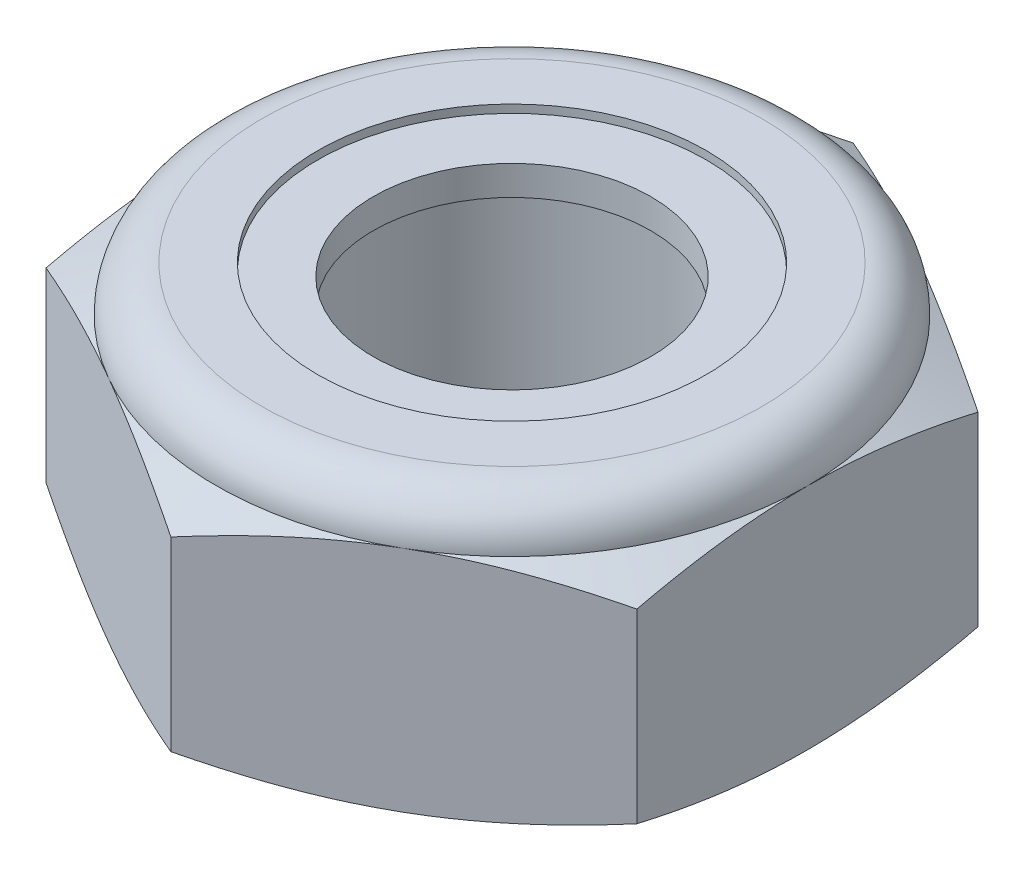
SolidWorks part; units mm, degrees
material "Plain Carbon Steel"
ref_plane "Front" through (0, 0, 0) normal (0, 0, 1) x (1, 0, 0)
ref_plane "Top" through (0, 0, 0) normal (0, 1, 0) x (1, 0, 0)
ref_plane "Right" through (0, 0, 0) normal (1, 0, 0) x (0, 0, -1)
sketch "Sketch1" plane through (0, 0, 0) normal (0, 1, 0) x (1, 0, 0)
  line L1 (0, 6.4158) -> (-5.5563, 3.2079)
  line L2 (-5.5563, 3.2079) -> (-5.5563, -3.2079)
  line L3 (-5.5563, -3.2079) -> (0, -6.4158)
  line L4 (0, -6.4158) -> (5.5562, -3.2079)
  line L5 (5.5562, -3.2079) -> (5.5562, 3.2079)
  line L6 (5.5562, 3.2079) -> (0, 6.4158)
  circle A0 centre (0, 0) radius 5.5563 construction
  dimension "Hex Flats" = 11.1125
extrude "Extrude1" add sketch "Sketch1" along normal blind 5.1594
sketch "Sketch2" plane through (0, 0, 0) normal (1, 0, 0) x (0, 0, -1)
  line L0 (-3.175, 0) -> (-3.175, 5.1594) construction
  line L1 (0, 0) -> (3.175, 0)
  line L2 (0, 0) -> (0, 5.1594)
  line L3 (0, 5.1594) -> (3.175, 5.1594)
  line L4 (3.175, 0) -> (3.175, 5.1594)
  line L5 (-3.2079, 5.1594) -> (3.2079, 5.1594) construction
  line L7 (0, -3.175) -> (0, 0) construction
  dimension "Thread Dia" = 6.35
revolve "Revolve1" add sketch "Sketch2" angle 360 about L7
sketch "Sketch3" plane through (0, 0, 0) normal (1, 0, 0) x (0, 0, -1)
  line L0 (3.175, 5.1594) -> (-3.175, 5.1594) construction
  line L1 (-3.175, 5.1594) -> (-3.175, 3.8894) construction
  line L2 (-3.175, 3.8894) -> (3.175, 5.1594) construction
  line L3 (3.175, 5.1594) -> (3.2061, 5.0037) construction
  line L4 (3.2061, 5.0037) -> (3.4241, 3.914)
  line L5 (3.4241, 3.914) -> (2.6722, 4.1684)
  line L6 (2.6722, 4.1684) -> (2.6099, 4.4797)
  line L7 (2.6099, 4.4797) -> (3.2061, 5.0037)
  line L8 (2.641, 4.3241) -> (3.3151, 4.4589) construction
  line L9 (3.175, 5.1594) -> (3.175, 4.4309) construction
  line L10 (3.175, 4.4309) -> (-3.175, 3.1609) construction
  line L11 (-3.175, 3.1609) -> (-3.175, 3.8894) construction
  line L12 (-0.2727, 5.1594) -> (0.2727, 2.4323) construction
  line L13 (-3.175, 0) -> (-3.175, 5.1594) construction
  line L14 (0, 5.1594) -> (3.175, 5.1594) construction
  line L15 (3.175, 0) -> (3.175, 5.1594) construction
  point P13 (0, 3.7959)
  dimension "D1" = 0.1588
  dimension "D2" = 0.3175
  dimension "Thread Pitch" = 1.27
  dimension "D4" = 60
  dimension "D5" = 1.27
sketch "Sketch4" plane through (0, 0, 0) normal (1, 0, 0) x (0, 0, -1)
  line L0 (0, 5.1594) -> (3.175, 5.1594)
  line L1 (3.175, 5.1594) -> (2.6099, 4.8959)
  line L2 (2.6099, 4.8959) -> (2.6099, 0.2635)
  line L3 (2.6099, 0.2635) -> (3.175, 0)
  line L4 (3.175, 0) -> (0, 0)
  line L5 (0, 0) -> (0, 5.1594)
  line L6 (3.175, 0) -> (3.175, 5.1594) construction
  line L7 (0, 5.1594) -> (3.175, 5.1594) construction
  line L8 (0, 0) -> (3.175, 0) construction
  line L9 (0, 0) -> (0, 5.1594) construction
  line L10 (0, 5.1594) -> (0, 5.7829) construction
  dimension "D1" = 25
combine bodies "Combine1" operation type subtract main body 108 bodies to subtract 109
sketch "Sketch5" plane through (0, 0, 0) normal (1, 0, 0) x (0, 0, -1)
  line L0 (0, 0) -> (5.5563, 0)
  line L1 (5.5563, 0) -> (6.4158, 0.4008)
  line L2 (6.4158, 0.4008) -> (6.4158, 3.8987)
  line L3 (6.4158, 3.8987) -> (5.5563, 4.2995)
  line L4 (4.6964, 5.1594) -> (4.6964, 6.4294)
  line L5 (4.6964, 6.4294) -> (7.6858, 6.4294)
  line L6 (7.6858, 6.4294) -> (7.6858, -1.27)
  line L7 (7.6858, -1.27) -> (0, -1.27)
  line L8 (0, -1.27) -> (0, 0)
  line L9 (5.5563, 4.2995) -> (5.5563, 0) construction
  line L10 (0, 0) -> (3.175, 0) construction
  line L13 (6.4158, 2.1497) -> (7.6858, 2.1497) construction
  line L14 (6.4158, 5.1594) -> (6.4158, 0) construction
  line L15 (0, 0) -> (0, 6.4294) construction
  line L20 (0, 6.4294) -> (4.6964, 6.4294) construction
  line L22 (0, 5.1594) -> (3.175, 5.1594) construction
  arc A0 (5.5563, 4.2995) -> (4.6964, 5.1594) centre (4.6964, 4.2995) ccw
  dimension "D1" = 25
  dimension "D2" = 1.27
  dimension "D3" = 5.1594
  dimension "D4" = 0.8599
revolve "Cut-Revolve3" cut sketch "Sketch5" angle 360 about L15
sketch "Sketch6" plane through (0, 0, 0) normal (1, 0, 0) x (0, 0, -1)
  line L0 (0, 4.2995) -> (5.4039, 4.2995)
  line L1 (4.6964, 5.007) -> (3.6531, 5.007)
  line L2 (0, 6.4294) -> (0, 4.2995)
  line L3 (3.6531, 6.4294) -> (0, 6.4294)
  line L4 (0, 6.4294) -> (4.6964, 6.4294) construction
  line L5 (0, 0) -> (0, 6.4294) construction
  line L6 (0, 6.4294) -> (0, 44.323) construction
  line L7 (3.6531, 5.007) -> (3.6531, 6.4294)
  line L8 (4.6964, 5.1594) -> (4.6964, 5.007) construction
  line L9 (3.6531, 5.007) -> (2.6099, 5.007) construction
  line L10 (2.6099, 5.007) -> (2.6099, 4.8959) construction
  arc A0 (5.4039, 4.2995) -> (4.6964, 5.007) centre (4.6964, 4.2995) ccw
  arc A1 (5.5563, 4.2995) -> (4.6964, 5.1594) centre (4.6964, 4.2995) ccw construction
  dimension "D1" = 0.1524
revolve "Cut-Revolve4" cut sketch "Sketch6" angle 360 about L6
sketch "Sketch7" plane through (0, 0, 0) normal (1, 0, 0) x (0, 0, -1)
  line L0 (2.6099, 4.3757) -> (5.323, 4.3757)
  line L1 (4.6964, 4.9308) -> (2.6099, 4.9308)
  line L2 (2.6099, 4.9308) -> (2.6099, 4.3757)
  line L3 (2.6099, 4.3757) -> (0, 4.3757) construction
  line L4 (0, 4.3757) -> (0, 4.9308) construction
  line L5 (0, 4.9308) -> (2.6099, 4.9308) construction
  line L6 (2.6099, 4.3757) -> (2.6099, 4.2995) construction
  line L7 (0, 4.2995) -> (5.4039, 4.2995) construction
  line L8 (4.6964, 4.9308) -> (4.6964, 5.007) construction
  arc A0 (5.323, 4.3757) -> (4.6964, 4.9308) centre (4.6964, 4.2995) ccw
  arc A2 (5.4039, 4.2995) -> (4.6964, 5.007) centre (4.6964, 4.2995) ccw construction
  dimension "D1" = 0.0762
revolve "Revolve2" add sketch "Sketch7" angle 360 about L4
equation "\"D1@Sketch3\"=\"Thread Pitch@Sketch3\"/8"
equation "\"D2@Sketch3\"=\"Thread Pitch@Sketch3\"/4"
equation "\"D5@Sketch3\"=\"Thread Pitch@Sketch3\""
equation "\"D4@Sketch5\"=\"Height@Extrude1\"/6"
